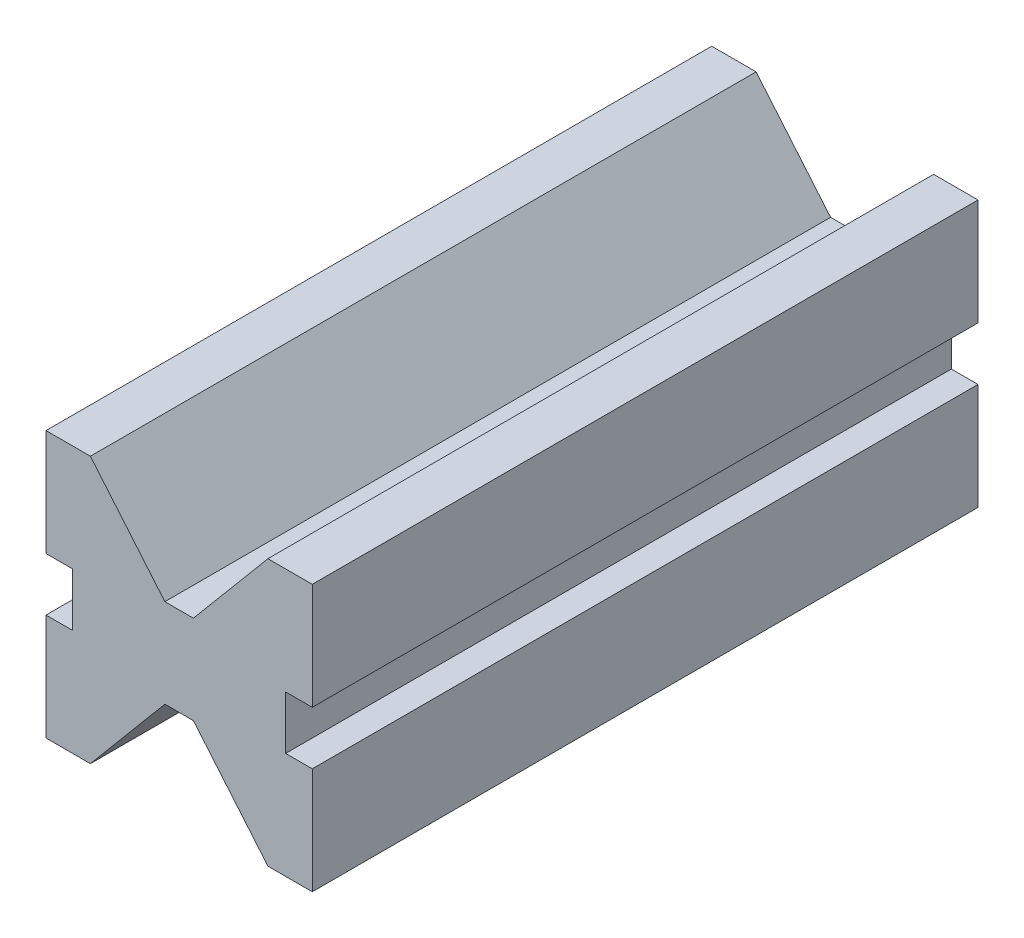
SolidWorks part; units mm, degrees
ref_plane "Front Plane" through (0, 0, 0) normal (0, 0, 1) x (1, 0, 0)
ref_plane "Top Plane" through (0, 0, 0) normal (0, 1, 0) x (1, 0, 0)
ref_plane "Right Plane" through (0, 0, 0) normal (1, 0, 0) x (0, 0, -1)
sketch "Sketch1" plane through (0, 0, 0) normal (0, 0, 1) x (1, 0, 0)
  line L0 (0, 0) -> (0, 24)
  line L1 (0, 24) -> (6, 24)
  line L2 (6, 24) -> (6, 36)
  line L3 (6, 36) -> (0, 36)
  line L4 (0, 36) -> (0, 60)
  line L5 (0, 60) -> (10, 60)
  line L6 (10, 60) -> (26.782, 40)
  line L7 (26.782, 40) -> (33.218, 40)
  line L8 (33.218, 40) -> (50, 60)
  line L9 (50, 60) -> (60, 60)
  line L10 (60, 60) -> (60, 36)
  line L11 (60, 36) -> (54, 36)
  line L12 (54, 36) -> (54, 24)
  line L13 (54, 24) -> (60, 24)
  line L14 (60, 24) -> (60, 0)
  line L15 (60, 0) -> (50, 0)
  line L16 (50, 0) -> (33.218, 20)
  line L17 (33.218, 20) -> (26.782, 20)
  line L18 (26.782, 20) -> (10, 0)
  line L19 (10, 0) -> (0, 0)
  point P19 (0, 0)
  point P22 (0, 0)
  dimension "D1" = 24
  dimension "D2" = 24
  dimension "D3" = 10
  dimension "D4" = 40
  dimension "D5" = 20
  dimension "D6" = 50
  dimension "D7" = 50
  dimension "D8" = 10
  dimension "D9" = 60
  dimension "D10" = 6
  dimension "D11" = 6
extrude "Boss-Extrude1" add sketch "Sketch1" along normal blind 150
